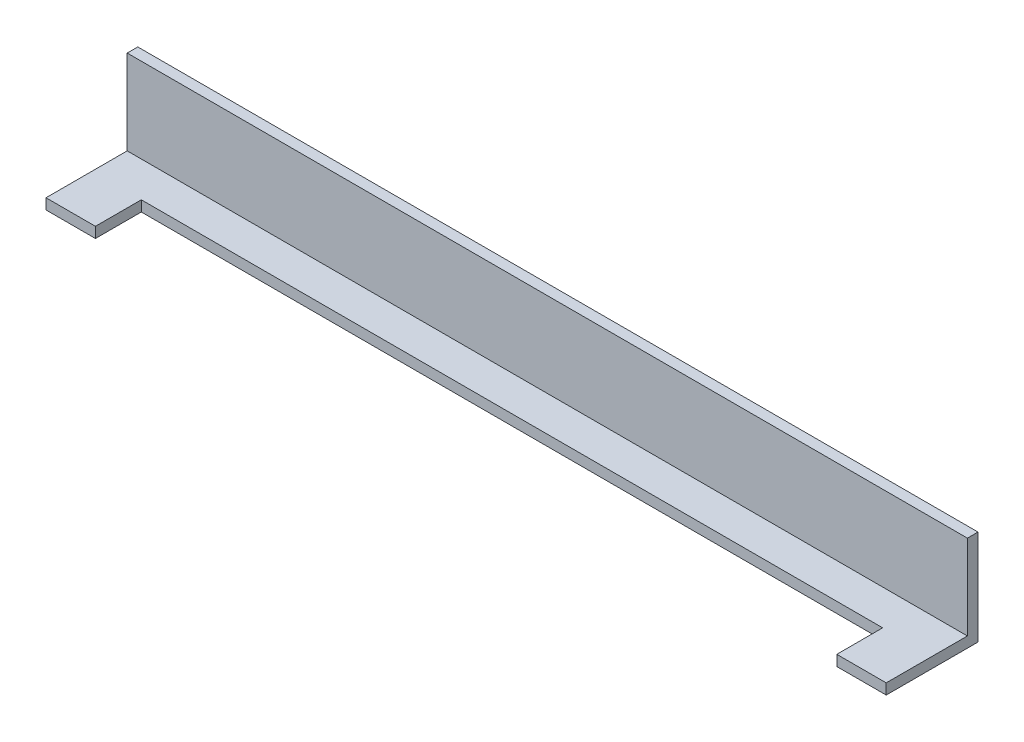
SolidWorks part; units mm, degrees
ref_plane "Front Plane" through (0, 0, 0) normal (0, 0, 1) x (1, 0, 0)
ref_plane "Top Plane" through (0, 0, 0) normal (0, 1, 0) x (1, 0, 0)
ref_plane "Right Plane" through (0, 0, 0) normal (1, 0, 0) x (0, 0, -1)
sketch "Sketch1" plane through (0, 0, 0) normal (0, 1, 0) x (1, 0, 0)
  line L1 (0, 0) -> (-238, 0)
  line L2 (0, 0) -> (0, -13)
  line L3 (0, -13) -> (-238, -13)
  line L4 (-238, 0) -> (-238, -13)
  dimension "D1" = 238
  dimension "D2" = 13
extrude "Boss-Extrude1" add sketch "Sketch1" along normal blind 3
sketch "Sketch2" plane through (0, 3, 0) normal (0, 1, 0) x (1, 0, 0)
  line L0 (-238, 0) -> (-238, -13) construction
  line L1 (0, 0) -> (-238, 0)
  line L2 (0, 0) -> (0, -3)
  line L3 (0, -3) -> (-238, -3)
  line L4 (-238, 0) -> (-238, -3)
  dimension "D1" = 3
extrude "Boss-Extrude2" add sketch "Sketch2" along normal blind 24
sketch "Sketch3" plane through (0, 0, 0) normal (0, -1, 0) x (1, 0, 0)
  line L1 (0, 0) -> (-14, 0)
  line L2 (0, 0) -> (0, 26)
  line L3 (0, 26) -> (-14, 26)
  line L4 (-14, 0) -> (-14, 26)
  dimension "D1" = 14
  dimension "D2" = 26
extrude "Boss-Extrude3" add sketch "Sketch3" against normal blind 3
sketch "Sketch5" plane through (0, 3, 0) normal (0, 1, 0) x (1, 0, 0)
  line L1 (-238, -3) -> (-224, -3)
  line L2 (-238, -3) -> (-238, -26)
  line L3 (-238, -26) -> (-224, -26)
  line L4 (-224, -3) -> (-224, -26)
  dimension "D1" = 23
  dimension "D2" = 14
extrude "Boss-Extrude5" add sketch "Sketch5" against normal blind 3
